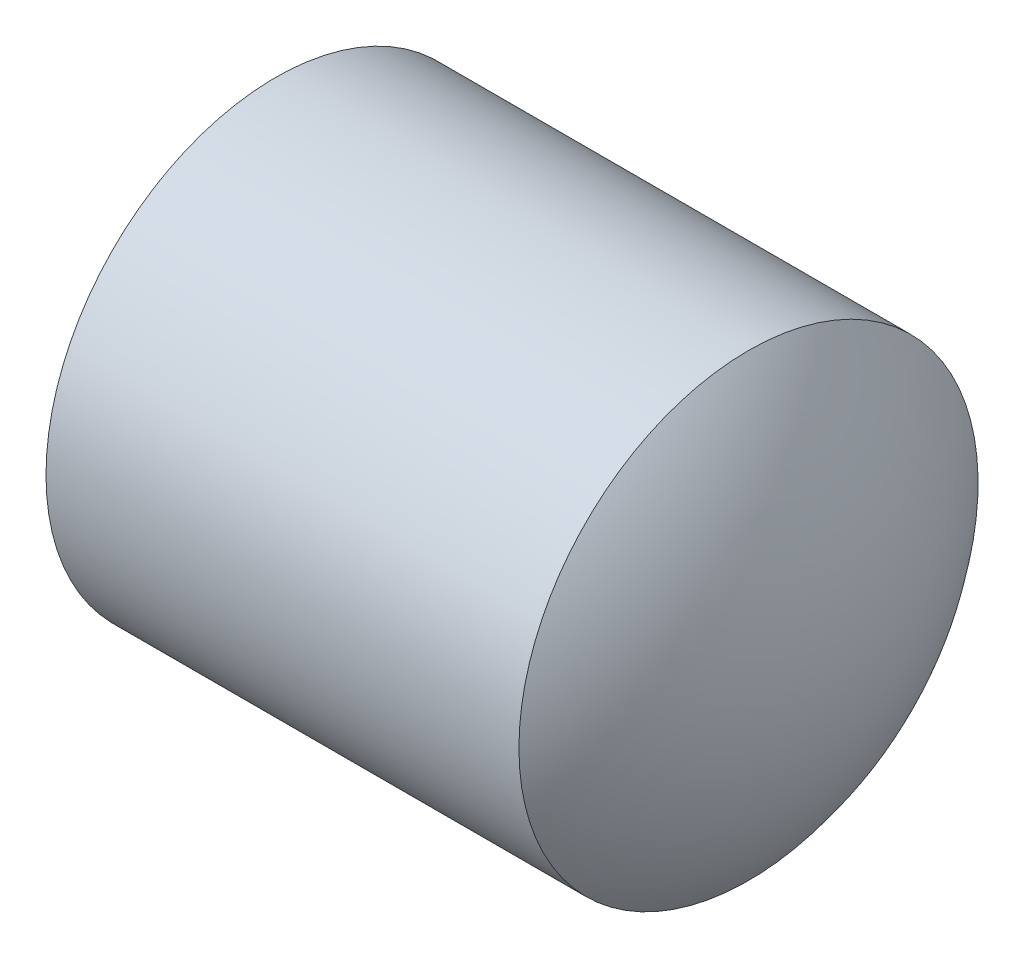
SolidWorks part; units mm, degrees
revolve "BaseBody" add sketch "BodySke" angle 360 about L5
sketch "BodySke" plane through (0, 0, 0) normal (0, 0, 1) x (1, 0, 0)
  line L0 (0, 0) -> (0, 10.352)
  line L1 (0, 10.352) -> (0.9515, 12)
  line L2 (0.9515, 12) -> (25.672, 12)
  line L3 (3, 15.875) -> (3, -3.175) construction
  line L4 (30, 0) -> (0, 0)
  line L5 (-12.7, 0) -> (88.9, 0) construction
  line L8 (0, -10.352) -> (0.9515, -12) construction
  arc A0 (30, 0) -> (25.672, 12) centre (11.2, 0) ccw
  dimension "Drive_ch_ang" = 60
cosmetic thread "ThreadCosmetic" [suppressed] parameters "Thread_minor"=2.439
ref_plane "Plane1" through (0, 0, 0) normal (0, 0, 1) x (1, 0, 0)
ref_plane "Plane2" through (0, 0, 0) normal (0, 1, 0) x (1, 0, 0)
ref_plane "Plane3" through (0, 0, 0) normal (1, 0, 0) x (0, 0, -1)
sketch "Sketch2" plane through (0, 0, 0) normal (-1, 0, 0) x (0, 0, 1)
  line L0 (3.4641, 6) -> (-3.4641, 6)
  line L1 (-3.4641, 6) -> (-6.9282, 0)
  line L2 (3.4641, 6) -> (6.9282, 0)
  line L3 (3.4641, -6) -> (6.9282, 0)
  line L4 (3.4641, -6) -> (-3.4641, -6)
  line L5 (-3.4641, -6) -> (-6.9282, 0)
  dimension "D2" = 0.75
  dimension "D3" = 0.75
extrude "Hex" cut sketch "Sketch2" against normal blind 12
sketch "Sketch4" plane through (0, 4.7709, -0.5249) normal (-1, 0, 0) x (0, 0, 1)
  line L0 (0.5249, -4.7709) -> (10.6976, -4.7709)
  line L1 (0.5249, -4.7709) -> (6.6732, -1.2211) construction
  line L2 (0.5249, -4.7709) -> (5.6112, 4.0389)
  line L3 (8.9666, -2.6687) -> (10.2861, -1.9069)
  line L4 (6.5663, 1.4888) -> (7.8858, 2.2506)
  arc A0 (8.9666, -2.6687) -> (6.5663, 1.4888) centre (0.5249, -4.7709) ccw
  arc A1 (10.6976, -4.7709) -> (10.2861, -1.9069) centre (0.5249, -4.7709) ccw
  arc A2 (5.6112, 4.0389) -> (7.8858, 2.2506) centre (0.5249, -4.7709) cw
  circle A3 centre (0.5249, -4.7709) radius 8.6995 construction
  circle A4 centre (0.5249, -4.7709) radius 10.1727 construction
  dimension "D1" = 30
  dimension "Spline_a_dim" = 60
  dimension "D3" = 0.178
extrude "Spline6" [suppressed] cut sketch "Sketch4" against normal blind 12
pattern_circular "CirPattern1" [suppressed] count 6 every 60 about axis through (-12.7, 0, 0) along (1, 0, 0)
sketch "Sketch5" plane through (0, -2.3417, -0.7053) normal (-1, 0, 0) x (0, 0, 1)
  line L0 (0.7053, 2.3417) -> (10.878, 2.3417)
  line L1 (0.7053, 2.3417) -> (5.7254, 7.3618) construction
  line L2 (0.7053, 2.3417) -> (0.7053, 12.5144)
  line L3 (8.554, 6.7959) -> (9.3926, 7.6345)
  line L4 (5.1595, 10.1904) -> (5.9981, 11.029)
  line L5 (5.1595, 10.1904) -> (8.554, 6.7959)
  arc A1 (10.878, 2.3417) -> (9.3926, 7.6345) centre (0.7053, 2.3417) ccw
  arc A2 (0.7053, 12.5144) -> (5.9981, 11.029) centre (0.7053, 2.3417) cw
  circle A3 centre (0.7053, 2.3417) radius 8.6995 construction
  circle A4 centre (0.7053, 2.3417) radius 10.1727 construction
  dimension "D3" = 0.178
  dimension "Spline_n_dim" = 1.295
  dimension "Spline_m_dim" = 1.575
  dimension "D1" = 45
  dimension "Spline_a_dim" = 90
  dimension "Spline_p_dim" = 0.356
extrude "Spline4" [suppressed] cut sketch "Sketch5" against normal blind 0.7
pattern_circular "CirPattern2" [suppressed] count 4 every 90 about axis through (-12.7, 0, 0) along (1, 0, 0)
sketch "ThdSchSke" plane through (0, 0, 0) normal (0, 0, 1) x (1, 0, 0)
  line L0 (0.9515, -10.352) -> (-0.2025, -12)
  line L1 (0.9515, -10.352) -> (2.1054, -12)
  line L2 (2.1054, -12) -> (2.1054, -15)
  line L3 (-3.175, 0) -> (5.1513, 0) construction
  line L4 (0.9515, 12) -> (0.9515, -12) construction
  line L5 (2.1054, -15) -> (-0.2025, -15)
  line L6 (-0.2025, -15) -> (-0.2025, -12)
  dimension "Thread_minor" = 2.439
  dimension "Diameter" = 3
revolve "ThreadSchematic" [suppressed] cut sketch "ThdSchSke" angle 360 about L3
pattern_linear "ThdSchPat" [suppressed]
equation "\"D2@Sketch2\" = \"Hex_size@Sketch2\" / 2"
equation "\"D3@Sketch2\" = \"Hex_size@Sketch2\" / 2"
equation "\"Thread_minor@ThreadCosmetic\" = \"Minor_dia@BodySke\""
equation "\"D1@Sketch4\" = \"Spline_a_dim@Sketch4\" / 2"
equation "\"D3@Sketch4\" = \"Spline_p_dim@Sketch4\" / 2"
equation "\"D2@CirPattern1\" = \"Spline_a_dim@Sketch4\""
equation "\"Num_teeth@CirPattern1\" = 360 / \"D2@CirPattern1\""
equation "\"Spline_a_dim@Sketch5\" = 90"
equation "\"Spline_p_dim@Sketch5\" = \"Spline_p_dim@Sketch4\""
equation "\"Spline_m_dim@Sketch5\" = \"Spline_m_dim@Sketch4\""
equation "\"Spline_n_dim@Sketch5\" = \"Spline_n_dim@Sketch4\""
equation "\"D1@Sketch5\" = \"Spline_a_dim@Sketch5\" / 2"
equation "\"D3@Sketch5\" = \"Spline_p_dim@Sketch5\" / 2"
equation "\"Key_eng@Spline4\" = \"Key_eng@Spline6\""
equation "\"Thread_minor@ThdSchSke\" = \"Thread_minor@ThreadCosmetic\""
equation "\"Diameter@ThdSchSke\" = \"Diameter@BodySke\""
equation "\"Overcut@ThdSchSke\" = \"Diameter@BodySke\" * 1.25"
equation "\"Num_threads@ThdSchPat\" = int( (\"Length@BodySke\" - ( ( ( \"Diameter@BodySke\" - \"Minor_dia@BodySke\" ) * 0.5 ) / tan( \"Drive_ch_ang@BodySke\" * 0.017453292 ) ) - ( \"Oval_radius@BodySke\" - sqr ( ( \"Oval_radius@BodySke\" * \"Oval_radius@BodySke\" ) - ( ( \"Diameter@BodySke\" * 0.5 ) * ( \"Diameter@BodySke\" * 0.5 ) ) ) ) ) / \"Advance@BodySke\" + 0.999 )  + 1"
equation "\"Advance@ThdSchPat\" = (\"Length@BodySke\" - ( ( ( \"Diameter@BodySke\" - \"Minor_dia@BodySke\" ) * 0.5 ) / tan( \"Drive_ch_ang@BodySke\" * 0.017453292 ) ) - ( \"Oval_radius@BodySke\" - sqr ( ( \"Oval_radius@BodySke\" * \"Oval_radius@BodySke\" ) - ( ( \"Diameter@BodySke\" * 0.5 ) * ( \"Diameter@BodySke\" * 0.5 ) ) ) ) ) /  (\"Num_threads@ThdSchPat\" - 1) 'relax it"
equation "' \"Num_threads@ThdSchPat\" = \"Num_threads@ThdSchPat\" - sgn( \"Num_threads@ThdSchPat\" - 1) '---chamfered tips only---"
